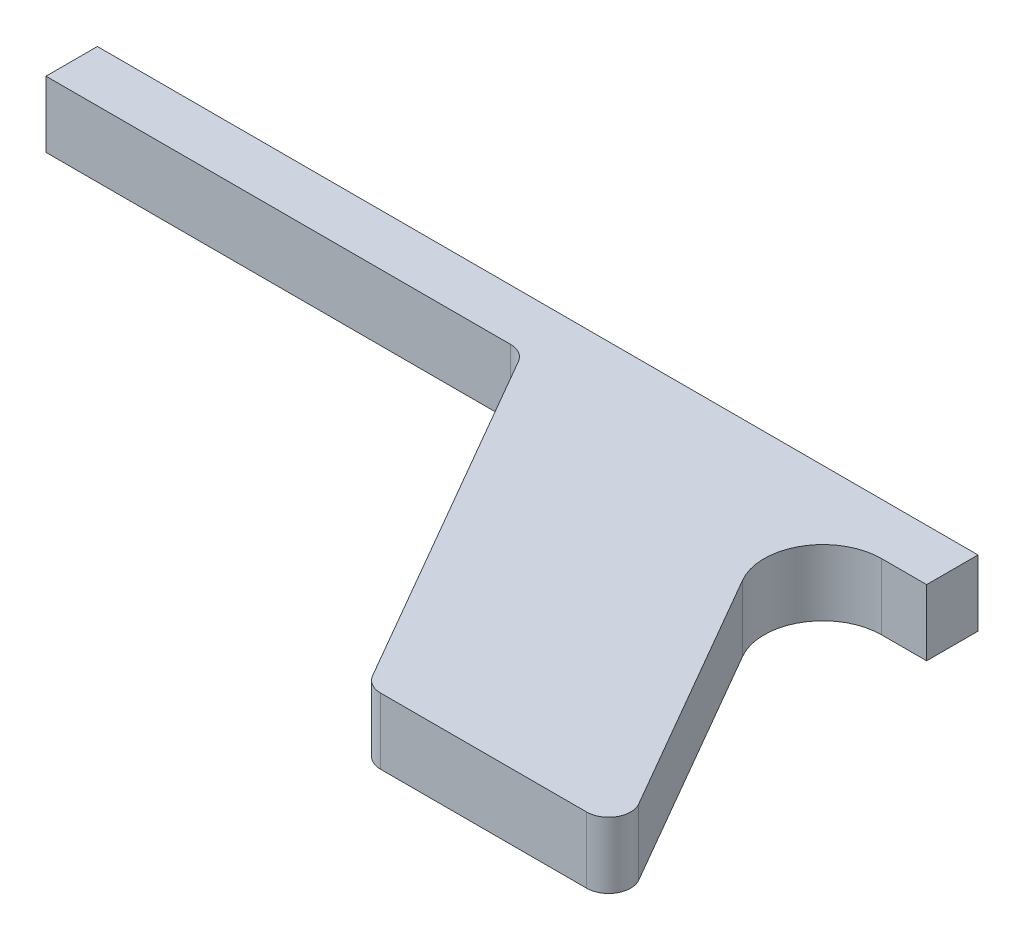
SolidWorks part; units mm, degrees
ref_plane "Front Plane" through (0, 0, 0) normal (0, 0, 1) x (1, 0, 0)
ref_plane "Top Plane" through (0, 0, 0) normal (0, 1, 0) x (1, 0, 0)
ref_plane "Right Plane" through (0, 0, 0) normal (1, 0, 0) x (0, 0, -1)
sketch "Sketch1" plane through (0, 0, 0) normal (0, 1, 0) x (1, 0, 0)
  line L0 (0, 0) -> (28.8675, -50)
  line L1 (0, 0) -> (35, 0)
  line L2 (28.8675, -50) -> (63.8675, -50)
  line L3 (35, 0) -> (63.8675, -50)
  line L5 (55, 0) -> (-65, 0)
  line L6 (55, 0) -> (55, 7)
  line L7 (55, 7) -> (-65, 7)
  line L8 (-65, 0) -> (-65, 7)
  dimension "D1" = 50
  dimension "D2" = 35
  dimension "D3" = 180
  dimension "D4" = 7
  dimension "D5" = 120
  dimension "D6" = 20
  dimension "D7" = 60
extrude "Boss-Extrude1" add sketch "Sketch1" along normal blind 9 contours L3 L1 L0 L2 | L8 L5 L1 L6 L7
fillet "Fillet1" radius 8 1 edges at (35, 4.5, 0)
fillet "Fillet2" radius 3 3 edges at (0, 4.5, 0) (28.8675, 4.5, 50) (63.8675, 4.5, 50)
